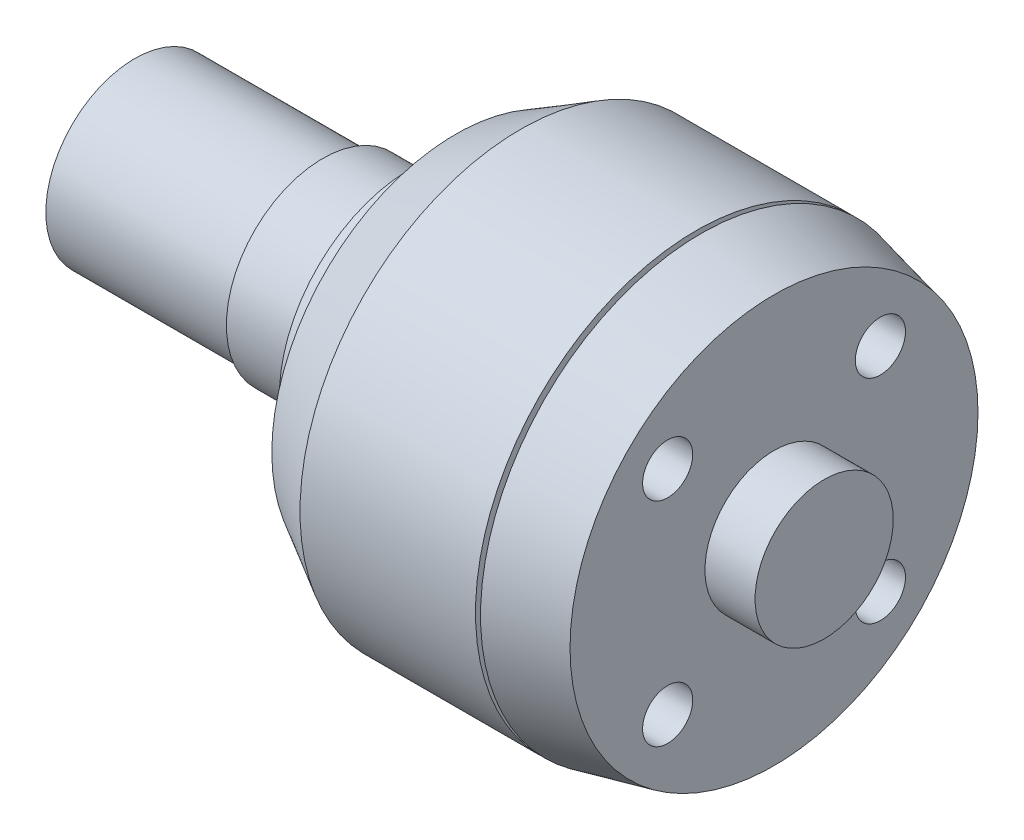
SolidWorks part; units mm, degrees
material "Alloy Steel"
ref_plane "Front Plane" through (0, 0, 0) normal (0, 0, 1) x (1, 0, 0)
ref_plane "Top Plane" through (0, 0, 0) normal (0, 1, 0) x (1, 0, 0)
ref_plane "Right Plane" through (0, 0, 0) normal (1, 0, 0) x (0, 0, -1)
sketch "Sketch2" plane through (0, 0, 0) normal (0, 1, 0) x (1, 0, 0)
  line L1 (-0.2959, 3.844) -> (-0.2959, 5.2314)
  line L3 (1.5041, 7.3312) -> (4.098, 8.8)
  line L5 (4.098, 8.8) -> (11.098, 8.8)
  line L6 (11.098, 8.8) -> (11.098, 7.0854)
  line L7 (11.098, 7.0854) -> (11.298, 7.0854)
  line L8 (11.298, 7.0854) -> (11.298, 8.8)
  line L9 (11.298, 8.8) -> (14.2041, 8.1363)
  line L10 (14.2041, 8.1363) -> (14.2041, 2.7551)
  line L11 (14.2041, 2.7551) -> (16.2041, 2.7551)
  line L12 (16.2041, 2.7551) -> (16.2041, 0)
  line L13 (16.2041, 0) -> (-11.2959, 0)
  line L14 (-11.2959, 0) -> (-11.2959, 3.5448)
  line L15 (-11.2959, 3.5448) -> (-3.7959, 3.5448)
  line L16 (-3.7959, 3.5448) -> (-3.7959, 3.844)
  line L17 (-3.7959, 3.844) -> (-0.2959, 3.844)
  line L18 (-0.2959, 5.2314) -> (1.5041, 5.2314)
  line L19 (1.5041, 5.2314) -> (1.5041, 7.3312)
  dimension "D1" = 8.8
  dimension "D2" = 11
  dimension "D3" = 7.5
  dimension "D4" = 1.8
  dimension "D5" = 25.5
  dimension "D6" = 2
  dimension "D7" = 0.2
  dimension "D8" = 7
revolve "Revolve1" add sketch "Sketch2" angle 360 about L13
sketch "Sketch3" plane through (14.2041, 0, 0) normal (1, 0, 0) x (0, 0, -1)
  line L1 (-4.2426, 4.2426) -> (4.2426, 4.2426) construction
  line L2 (-4.2426, 4.2426) -> (-4.2426, -4.2426) construction
  line L3 (-4.2426, -4.2426) -> (4.2426, -4.2426) construction
  line L4 (4.2426, 4.2426) -> (4.2426, -4.2426) construction
  circle A0 centre (0, 0) radius 6 construction
  circle A1 centre (4.2426, 4.2426) radius 1
  circle A2 centre (4.2426, -4.2426) radius 1
  circle A3 centre (-4.2426, -4.2426) radius 1
  circle A4 centre (-4.2426, 4.2426) radius 1
  dimension "D1" = 12
  dimension "D2" = 2
extrude "Cut-Extrude1" cut sketch "Sketch3" against normal blind 2
